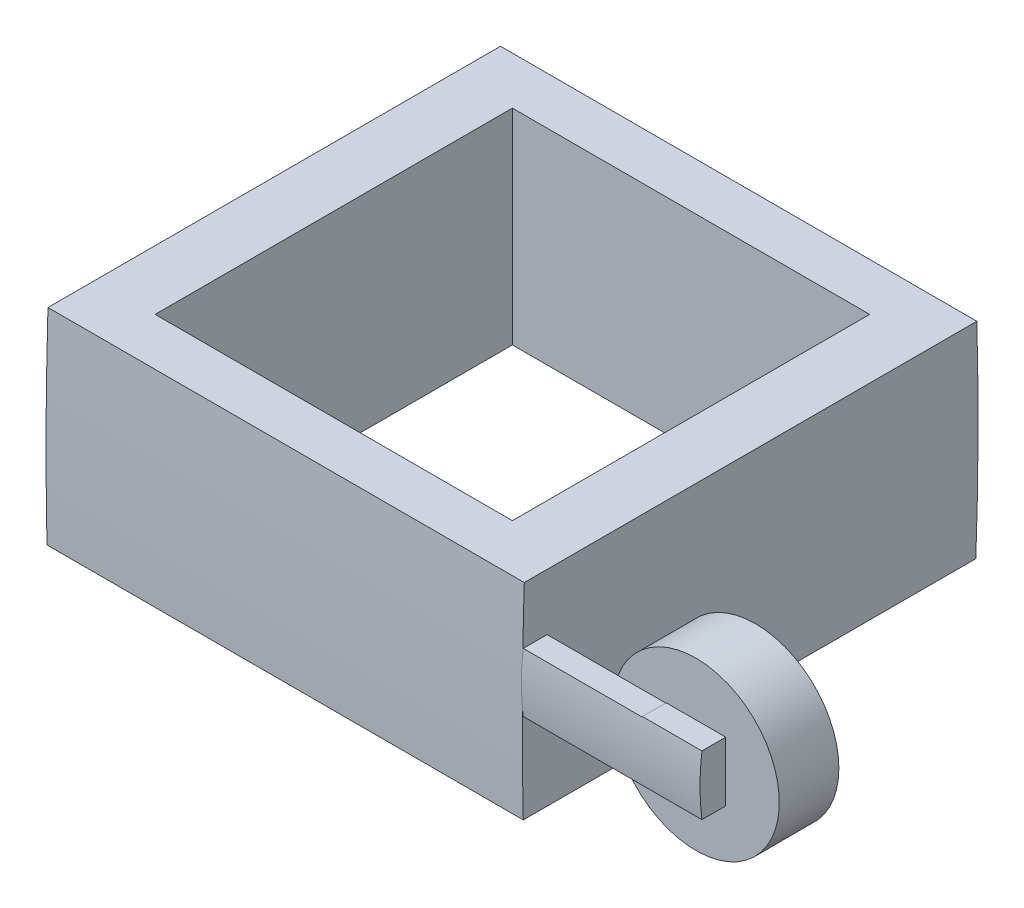
SolidWorks part; units mm, degrees
ref_plane "Front Plane" through (0, 0, 0) normal (0, 0, 1) x (1, 0, 0)
ref_plane "Top Plane" through (0, 0, 0) normal (0, 1, 0) x (1, 0, 0)
ref_plane "Right Plane" through (0, 0, 0) normal (1, 0, 0) x (0, 0, -1)
sketch "Sketch1" plane through (0, 0, 0) normal (0, 0, 1) x (1, 0, 0)
  circle A0 centre (0, 0) radius 14
  circle A1 centre (0, 0) radius 10
  circle A2 centre (0, 0) radius 5.5
extrude "Boss-Extrude1" add sketch "Sketch1" along normal blind 10 contours A0
sketch "Sketch2" plane through (0, 0, 0) normal (0, 0, -1) x (-1, 0, 0)
  circle A0 centre (0, 0) radius 2.25
extrude "Cut-Extrude1" cut sketch "Sketch2" against normal blind 5
sketch "Sketch3" plane through (0, 0, 0) normal (0, 0, -1) x (-1, 0, 0)
  circle A0 centre (0, 0) radius 5
extrude "Cut-Extrude2" cut sketch "Sketch3" against normal blind 1.8
sketch "Sketch4" plane through (0, 0, 10) normal (0, 0, 1) x (1, 0, 0)
  line L1 (-5, 5) -> (5, 5)
  line L2 (-5, 5) -> (-5, -5)
  line L3 (-5, -5) -> (5, -5)
  line L4 (5, 5) -> (5, -5)
  line L5 (-5, 5) -> (5, -5) construction
  line L6 (-5, -5) -> (5, 5) construction
  point P0 (0, 0)
  dimension "D1" = 10
  dimension "D2" = 10
extrude "Boss-Extrude2" add sketch "Sketch4" along normal blind 8
sketch "Sketch6" plane through (-5, 0, 0) normal (-1, 0, 0) x (0, 0, 1)
  line L0 (10, 5) -> (10, -5) construction
  line L1 (10, 4.9129) -> (18, 4.9129)
  line L2 (10, 4.9129) -> (10, -5)
  line L3 (10, -5) -> (18, -5)
  line L4 (18, 4.9129) -> (18, -5)
extrude "Boss-Extrude3" add sketch "Sketch6" along normal blind 20
sketch "Sketch7" plane through (5, 0, 0) normal (1, 0, 0) x (0, 0, -1)
  line L0 (-18, 5) -> (-18, -5)
  line L1 (-18, -5) -> (-14, -5)
  line L2 (-18, -5) -> (-10, -5) construction
  line L3 (-18, 5) -> (-14, 5)
  line L4 (-18, 5) -> (-10, 5) construction
  arc A2 (-14, -5) -> (-14, 5) centre (23.6696, 0) cw
extrude "Cut-Extrude3" cut sketch "Sketch7" against normal blind 30
sketch "Sketch8" plane through (-25, 0, 0) normal (-1, 0, 0) x (0, 0, 1)
  line L4 (-62.1689, 14.4036) -> (13.8311, 14.4036)
  line L5 (-62, -20.0436) -> (14, -20.0436)
  arc A0 (13.8311, 14.4036) -> (14, -20.0436) centre (-602.0691, -5.8394) cw
  arc A1 (-62, -20.0436) -> (-62.1689, 14.4036) centre (468.3236, -0.2201) cw
  dimension "D1" = 76
  dimension "D2" = 76
extrude "Boss-Extrude4" add sketch "Sketch8" along normal blind 80
sketch "Sketch9" plane through (0, 14.4036, 0) normal (0, 1, 0) x (1, 0, 0)
  line L1 (-35, -5.8311) -> (-95, -5.8311)
  line L2 (-35, -5.8311) -> (-35, 54.1689)
  line L3 (-35, 54.1689) -> (-95, 54.1689)
  line L4 (-95, -5.8311) -> (-95, 54.1689)
  line L5 (-35, -5.8311) -> (-95, 54.1689) construction
  line L6 (-35, 54.1689) -> (-95, -5.8311) construction
  point P0 (-65, 24.1689)
  point P17 (-65, 24.1689)
extrude "Cut-Extrude4" cut sketch "Sketch9" against normal blind 100
